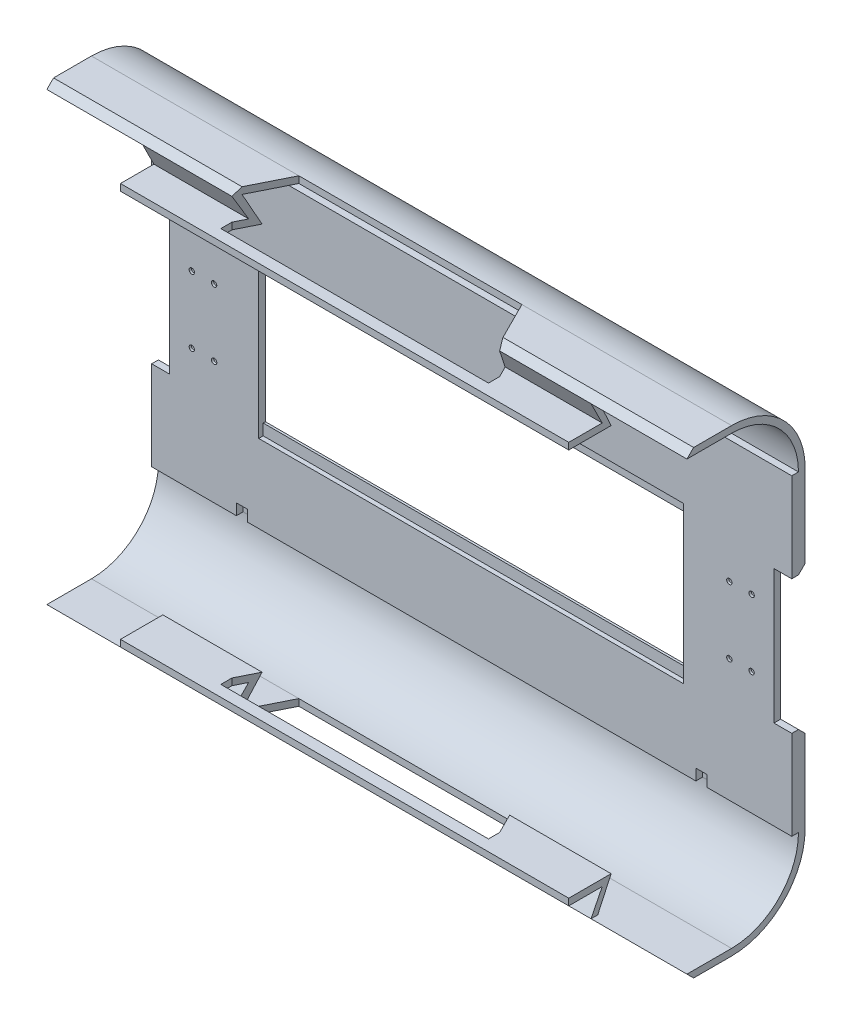
SolidWorks part; units mm, degrees
ref_plane "前视基准面" through (0, 0, 0) normal (0, 0, 1) x (1, 0, 0)
ref_plane "上视基准面" through (0, 0, 0) normal (0, 1, 0) x (1, 0, 0)
ref_plane "右视基准面" through (0, 0, 0) normal (1, 0, 0) x (0, 0, -1)
sketch "草图1" plane through (0, 0, 0) normal (0, 0, 1) x (1, 0, 0)
  line L61 (-143.25, 30) -> (-143.25, 70)
  line L65 (-135.25, 30) -> (-143.25, 30)
  line L80 (-105.25, 65) -> (-105.25, 70)
  line L81 (-143.25, 70) -> (-105.25, 70)
  line L109 (-105.25, 65) -> (-100.25, 65)
  line L110 (-100.25, 65) -> (-100.25, 70)
  line L112 (-100.25, 70) -> (100.75, 70)
  line L115 (-135.25, -30) -> (-135.25, 30)
  line L116 (135.75, -30) -> (135.75, 30)
  line L117 (100.75, 65) -> (100.75, 70)
  line L118 (105.75, 65) -> (100.75, 65)
  line L119 (143.75, 70) -> (105.75, 70)
  line L120 (105.75, 65) -> (105.75, 70)
  line L121 (135.75, 30) -> (143.75, 30)
  line L122 (143.75, 30) -> (143.75, 70)
  line L123 (143.75, -30) -> (143.75, -70)
  line L124 (135.75, -30) -> (143.75, -30)
  line L125 (105.75, -65) -> (105.75, -70)
  line L126 (143.75, -70) -> (105.75, -70)
  line L127 (105.75, -65) -> (100.75, -65)
  line L128 (100.75, -65) -> (100.75, -70)
  line L129 (-100.25, -70) -> (100.75, -70)
  line L130 (-100.25, -65) -> (-100.25, -70)
  line L131 (-105.25, -65) -> (-100.25, -65)
  line L132 (-143.25, -70) -> (-105.25, -70)
  line L133 (-105.25, -65) -> (-105.25, -70)
  line L134 (-135.25, -30) -> (-143.25, -30)
  line L135 (-143.25, -30) -> (-143.25, -70)
  point P23 (135.75, 0)
extrude "凸台-拉伸1" add sketch "草图1" along normal blind 3
ref_plane "基准面1" through (-143.25, 0, 0) normal (-1, 0, 0) x (0, 0, 1)
sketch "草图2" plane through (-143.25, 0, 0) normal (-1, 0, 0) x (0, 0, 1)
  line L1 (0, 70) -> (0, 30)
  line L2 (0, 30) -> (-3, 33)
  line L3 (-3, 33) -> (-3, 70)
  line L4 (50, 100) -> (47, 103)
  line L8 (30, 103) -> (47, 103)
  line L17 (45, 90) -> (50, 100)
  line L18 (45, 90) -> (60, 90)
  line L19 (60, 90) -> (60, 87)
  line L20 (60, 87) -> (41, 87)
  line L21 (41, 87) -> (47, 100)
  line L22 (30, 100) -> (47, 100)
  line L24 (30, -100) -> (47, -100)
  line L25 (41, -87) -> (47, -100)
  line L26 (60, -87) -> (41, -87)
  line L27 (60, -90) -> (60, -87)
  line L28 (45, -90) -> (60, -90)
  line L29 (45, -90) -> (50, -100)
  line L30 (30, -103) -> (47, -103)
  line L31 (50, -100) -> (47, -103)
  line L32 (-3, -33) -> (-3, -70)
  line L33 (0, -30) -> (-3, -33)
  line L34 (0, -70) -> (0, -30)
  arc A0 (0, 70) -> (30, 100) centre (30, 70) cw
  arc A1 (-3, 70) -> (30, 103) centre (30, 70) cw
  arc A4 (-3, -70) -> (30, -103) centre (30, -70) ccw
  arc A5 (0, -70) -> (30, -100) centre (30, -70) ccw
extrude "凸台-拉伸2" add sketch "草图2" against normal blind 287
sketch "草图4" plane through (-143.25, 0, 0) normal (-1, 0, 0) x (0, 0, 1)
  line L1 (30, 100) -> (47, 100) construction
  line L4 (60.2366, -100) -> (38.5, -100)
  line L5 (60.2366, -100) -> (60.2366, 100)
  line L6 (60.2366, 100) -> (38.5, 100)
  line L7 (38.5, -100) -> (38.5, 100)
extrude "切除-拉伸1" cut sketch "草图4" against normal blind 43
ref_plane "基准面2" through (143.75, 0, 0) normal (1, 0, 0) x (0, 0, -1)
sketch "草图5" plane through (143.75, 0, 0) normal (1, 0, 0) x (0, 0, -1)
  line L1 (-30, 100) -> (-47, 100) construction
  line L4 (-63.1672, -100) -> (-39.752, -100)
  line L5 (-63.1672, -100) -> (-63.1672, 100)
  line L6 (-63.1672, 100) -> (-39.752, 100)
  line L7 (-39.752, -100) -> (-39.752, 100)
extrude "切除-拉伸2" cut sketch "草图5" against normal blind 43
ref_plane "基准面3" through (0, 103, 0) normal (0, 1, 0) x (1, 0, 0)
sketch "草图6" plane through (0, 103, 0) normal (0, 1, 0) x (1, 0, 0)
  line L1 (143.75, -30) -> (-143.25, -30) construction
  line L2 (100.75, -50) -> (-100.25, -50) construction
  line L3 (0.25, -30) -> (-50.25, -30)
  line L4 (0.25, -30) -> (49.75, -30)
  line L7 (-50.25, -30) -> (-60.25, -50)
  line L8 (-60.25, -50) -> (-60.25, -55)
  line L9 (-60.25, -55) -> (59.75, -55)
  line L10 (59.75, -55) -> (59.75, -50)
  line L11 (59.75, -50) -> (49.75, -30)
extrude "切除-拉伸3" cut sketch "草图6" against normal through all
hole_wizard "大小六角凹头盖螺钉柱孔1" positions "3D草图3" profile "草图9" counterbore size "M2" standard "AS" end condition through all
sketch3d "3D草图3"
  line L0 (135.75, 0, 0) -> (125.75, 0, 0)
  line L1 (135.75, -30, 0) -> (135.75, 30, 0) construction
  line L3 (125.75, 0, 0) -> (125.75, 15, 0)
  line L5 (125.75, 0, 0) -> (125.75, -15, 0)
  point P15 (125.75, -15, 0)
  point P17 (125.75, 15, 0)
  point P26 (-125.25, -15, 0)
  point P31 (-125.25, 15, 0)
  point P39 (-115.25, -15, 0)
  point P44 (-115.25, 15, 0)
  point P48 (115.75, -15, 0)
  point P50 (115.75, 15, 0)
  point P52 (0, 0, 0)
  point P53 (0, 0, 0)
  point P54 (0, 0, 0)
sketch "草图9" plane through (115.75, 15, 0) normal (1, 0, 0) x (0, 1, 0)
  line L0 (0, 0) -> (0, 60)
  line L1 (0, 60) -> (1.2, 60)
  line L3 (1.2, 60) -> (1.2, 2)
  line L4 (2.15, 2) -> (1.2, 2)
  line L5 (2.15, 2) -> (2.15, 0.0241)
  line L6 (2.15, 0.0241) -> (2.175, 0)
  line L7 (2.175, 0) -> (0, 0)
  line L8 (-2.15, 0.0241) -> (-2.175, 0) construction
  line L11 (0, -6.35) -> (0, 107.95) construction
  dimension "通孔孔直径" = 2.4
  dimension "通孔孔深度" = 60
  dimension "柱形沉头孔直径" = 4.3
  dimension "柱形沉头孔深度" = 2
  dimension "近端锥形沉头孔直径" = 4.35
  dimension "近端锥形沉头孔角度" = 92
ref_plane "基准面5" through (0, 0, 3) normal (0, 0, 1) x (1, 0, 0)
sketch "草图10" plane through (0, 0, 3) normal (0, 0, 1) x (1, 0, 0)
  line L0 (-95.25, -35) -> (-95.25, 35)
  line L2 (-95.25, -35) -> (95.25, -35)
  line L4 (-95.25, 35) -> (95.25, 35)
  line L5 (95.25, -35) -> (95.25, 35)
  point P8 (0, 35)
extrude "切除-拉伸4" cut sketch "草图10" against normal blind 2
sketch "草图11" plane through (0, 0, 0) normal (0, 0, 1) x (1, 0, 0)
  line L0 (-95.25, 30) -> (-95.25, -30)
  line L1 (-95.25, 35) -> (-95.25, -35) construction
  line L2 (-95.25, 30) -> (95.25, 30)
  line L5 (95.25, 30) -> (95.25, -30)
  line L6 (-95.25, -30) -> (95.25, -30)
  point P10 (95.25, 0)
extrude "切除-拉伸5" cut sketch "草图11" along normal blind 1
